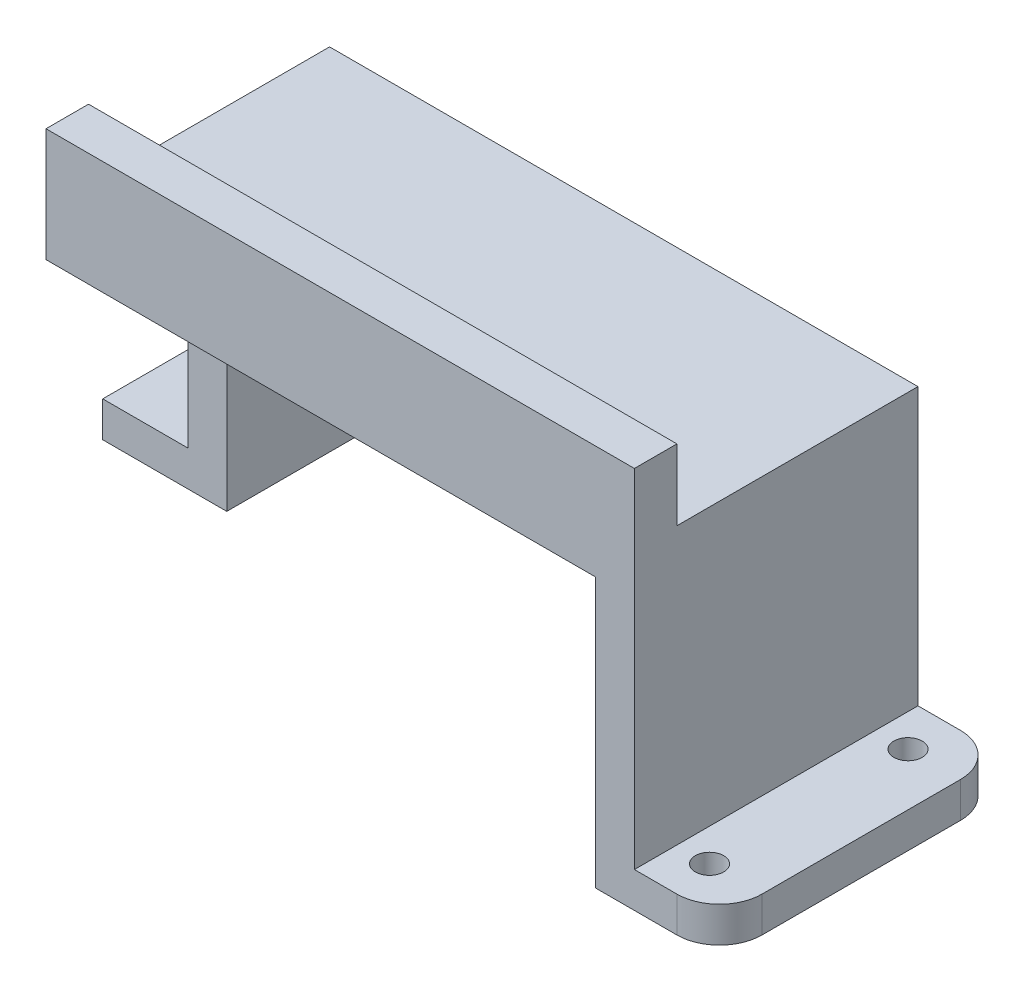
SolidWorks part; units mm, degrees
ref_plane "Front Plane" through (0, 0, 0) normal (0, 0, 1) x (1, 0, 0)
ref_plane "Top Plane" through (0, 0, 0) normal (0, 1, 0) x (1, 0, 0)
ref_plane "Right Plane" through (0, 0, 0) normal (1, 0, 0) x (0, 0, -1)
sketch "Sketch1" plane through (0, 0, 0) normal (0, 0, 1) x (1, 0, 0)
  line L0 (19, -20) -> (21.75, -20)
  line L1 (-19.75, -20) -> (-17, -20)
  line L2 (-19.75, -20) -> (-19.75, 2)
  line L3 (-19.75, 2) -> (21.75, 2)
  line L4 (21.75, -20) -> (21.75, 2)
  line L8 (-17, -20) -> (-17, -1)
  line L9 (-17, -1) -> (19, -1)
  line L10 (19, -20) -> (19, -1)
  dimension "D1" = 22
  dimension "D2" = 41.5
  dimension "D3" = 19
  dimension "D4" = 2.75
  dimension "D5" = 36
extrude "Boss-Extrude1" add sketch "Sketch1" along normal blind 33.5
sketch "Sketch2" plane through (21.75, 0, 0) normal (1, 0, 0) x (0, 0, -1)
  line L1 (-33.5, -20) -> (0, -20) construction
  line L3 (-33.5, -20) -> (-33.5, -17.5)
  line L4 (-33.5, -17.5) -> (-13.5, -17.5)
  line L5 (-13.5, -20) -> (-13.5, -17.5)
  line L9 (-33.5, -20) -> (-13.5, -20)
  point P0 (-16.75, -20)
  dimension "D1" = 2.5
extrude "Boss-Extrude2" add sketch "Sketch2" along normal blind 6
sketch "Sketch9" plane through (0, -17.5, 0) normal (0, 1, 0) x (1, 0, 0)
  line L0 (27.75, -13.5) -> (21.75, -13.5) construction
  line L1 (21.75, -13.5) -> (21.75, -33.5) construction
  circle A0 centre (24.05, -16.5) radius 1
  circle A1 centre (24.05, -30.5) radius 1
  dimension "D1" = 14
  dimension "D2" = 3
  dimension "D3" = 2.3
  dimension "D4" = 2.3
ref_plane "Plane1" through (0, 0, 16.75) normal (0, 0, 1) x (1, 0, 0)
ref_plane "Plane2" through (2.75, 0, 0) normal (1, 0, 0) x (0, 0, -1)
extrude "Corte-extrusão1" cut sketch "Sketch9" against normal through all
fillet "Filete1" radius 3 2 edges at (27.75, -18.75, 13.5) (27.75, -18.75, 33.5)
sketch "Esboço8" plane through (0, 0, 33.5) normal (0, 0, 1) x (1, 0, 0)
  line L0 (19, -20) -> (24.75, -20) construction
  line L1 (19, -1) -> (19.75, -1)
  line L2 (19, -1) -> (19, -20)
  line L3 (19, -20) -> (19.75, -20)
  line L4 (19.75, -1) -> (19.75, -20)
  line L6 (-17, -1) -> (-17.75, -1)
  line L7 (-17, -1) -> (-17, -15)
  line L8 (-17, -15) -> (-17.75, -15)
  line L9 (-17.75, -1) -> (-17.75, -15)
  dimension "D1" = 0.75
  dimension "D2" = 0.75
sketch "Esboço12" plane through (0, 2, 0) normal (0, 1, 0) x (1, 0, 0)
  line L0 (21.75, -33.5) -> (21.75, 0) construction
  line L1 (-19.75, -33.5) -> (21.75, -33.5)
  line L2 (-19.75, -33.5) -> (-19.75, -30.5)
  line L3 (-19.75, -30.5) -> (21.75, -30.5)
  line L4 (21.75, -33.5) -> (21.75, -30.5)
  dimension "D1" = 3
extrude "Ressalto-extrusão1" add sketch "Esboço12" along normal blind 5
ref_plane "Plano1" through (1, 0, 0) normal (1, 0, 0) x (0, 0, -1)
mirror "Espelhar1" about plane through (1, 0, 0) normal (1, 0, 0) of "Corte-extrusão1", "Filete1", "Boss-Extrude2"
sketch "Esboço14" plane through (0, 0, 33.5) normal (0, 0, 1) x (1, 0, 0)
  line L1 (-17, -20) -> (-29, -20)
  line L2 (-17, -20) -> (-17, -0.9973)
  line L3 (-17, -0.9973) -> (-29, -0.9973)
  line L4 (-29, -20) -> (-29, -0.9973)
  dimension "D1" = 12
extrude "Corte-extrusão10" cut sketch "Esboço14" against normal blind 10
sketch "Esboço15" plane through (-19.75, 0, 0) normal (-1, 0, 0) x (0, 0, 1)
  line L0 (0, -20) -> (13.5, -20)
  line L1 (0, -20) -> (0, 2.0813)
  line L2 (13.5, -20) -> (13.5, 2.0813)
  line L3 (0, 2.0813) -> (13.5, 2.0813)
extrude "Corte-extrusão11" cut sketch "Esboço15" against normal through all
